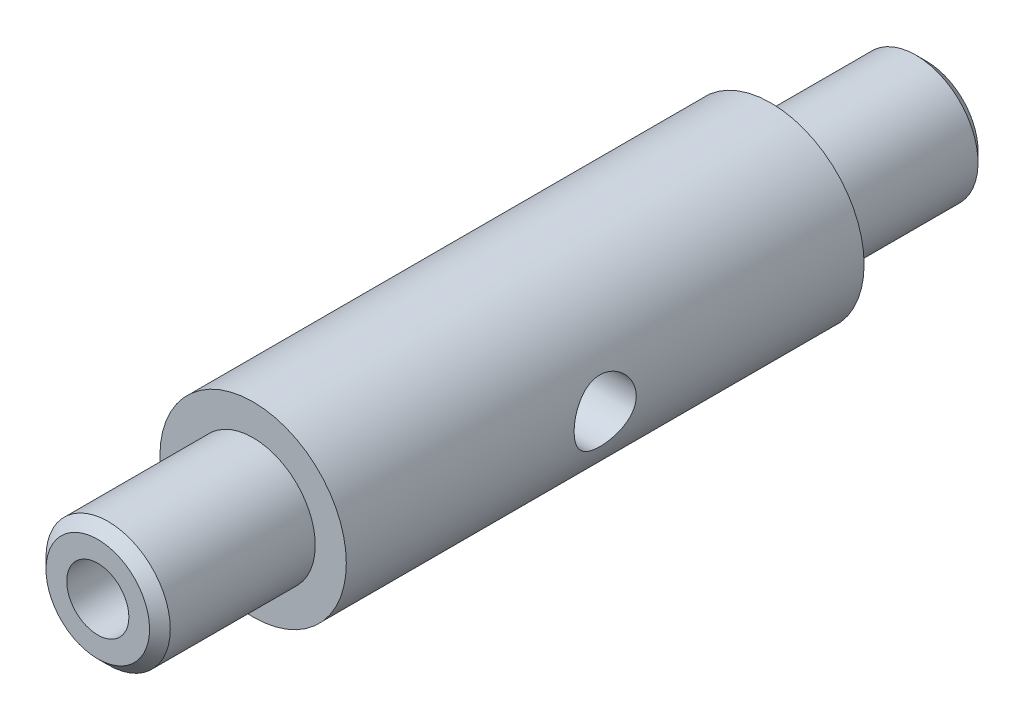
SolidWorks part; units mm, degrees
ref_plane "Front Plane" through (0, 0, 0) normal (0, 0, 1) x (1, 0, 0)
ref_plane "Top Plane" through (0, 0, 0) normal (0, 1, 0) x (1, 0, 0)
ref_plane "Right Plane" through (0, 0, 0) normal (1, 0, 0) x (0, 0, -1)
sketch "Sketch1" plane through (0, 0, 0) normal (1, 0, 0) x (0, 0, -1)
  line L0 (0, 0) -> (0, 6)
  line L1 (0, 6) -> (15, 6)
  line L2 (15, 6) -> (15, 9)
  line L3 (15, 9) -> (65, 9)
  line L4 (65, 9) -> (65, 6)
  line L5 (65, 6) -> (80, 6)
  line L6 (80, 6) -> (80, 0)
  line L7 (80, 0) -> (0, 0)
  dimension "D1" = 50
  dimension "D2" = 6
  dimension "D3" = 9
  dimension "D4" = 15
  dimension "D5" = 80
revolve "Revolve1" add sketch "Sketch1" angle 360 about L7
hole_wizard "Hole1" positions "Sketch2" profile "Sketch3" legacy
sketch "Sketch2" plane through (0, 0, 0) normal (0, 0, 1) x (1, 0, 0)
  point P0 (0, 0)
sketch "Sketch3" plane through (0, 0, 0) normal (1, 0, 0) x (0, -1, 0)
  line L0 (0, 0) -> (0, 45)
  line L1 (0, 45) -> (3, 45)
  line L2 (3, 45) -> (3, 0)
  line L3 (3, 0) -> (0, 0)
  line L4 (0, 110) -> (0, -10) construction
  dimension "Diameter" = 6
  dimension "Depth" = 45
sketch "Sketch4" plane through (0, 0, 0) normal (1, 0, 0) x (0, 0, -1)
  line L0 (15, 6) -> (15, -6) construction
  circle A0 centre (40, 0) radius 3
  point P4 (0, 0)
  dimension "D1" = 6
  dimension "D2" = 25
extrude "Cut-Extrude1" cut sketch "Sketch4" against normal through all both and the other way through all
chamfer "Chamfer1" distance 1 angle 45 2 edges at (0, 6, -80) (0, 6, 0)
